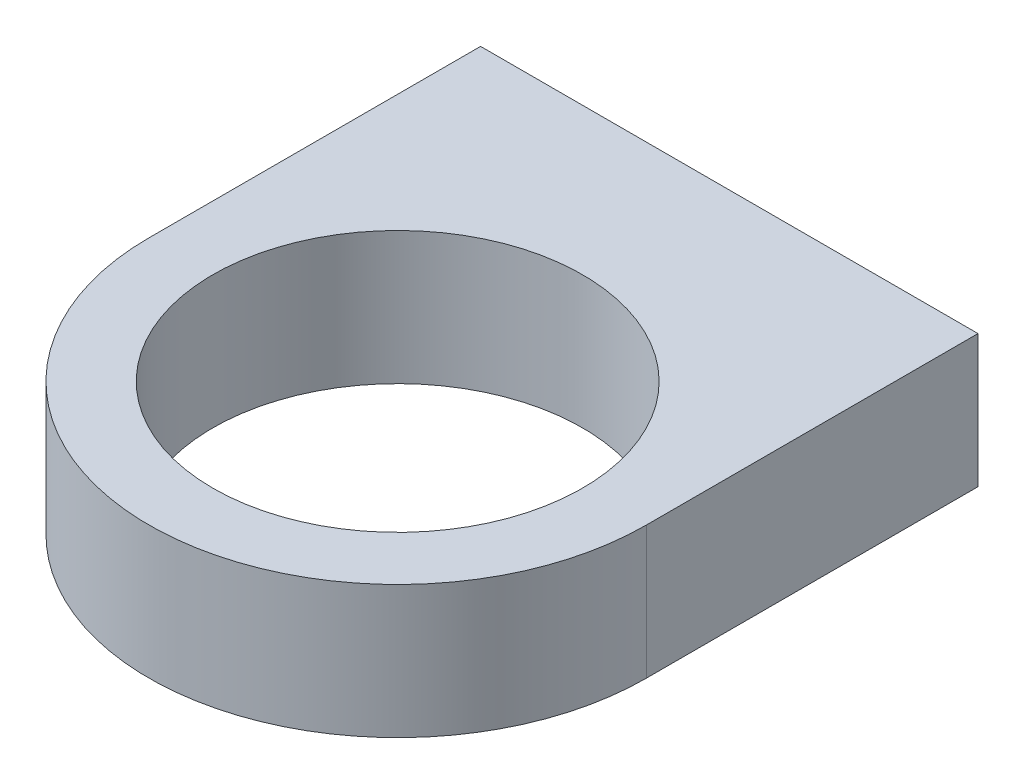
SolidWorks part; units mm, degrees
ref_plane "Alzado" through (0, 0, 0) normal (0, 0, 1) x (1, 0, 0)
ref_plane "Planta" through (0, 0, 0) normal (0, 1, 0) x (1, 0, 0)
ref_plane "Vista lateral" through (0, 0, 0) normal (1, 0, 0) x (0, 0, -1)
sketch "Croquis1" plane through (0, 0, 0) normal (0, 1, 0) x (1, 0, 0)
  line L0 (-15, 0) -> (-15, 20)
  line L1 (-15, 20) -> (15, 20)
  line L2 (15, 20) -> (15, 0)
  circle A0 centre (0, 0) radius 11.15
  arc A1 (-15, 0) -> (15, 0) centre (0, 0) ccw
  dimension "D1" = 22.3
  dimension "D2" = 30
  dimension "D3" = 20
extrude "Saliente-Extruir1" add sketch "Croquis1" along normal blind 8
